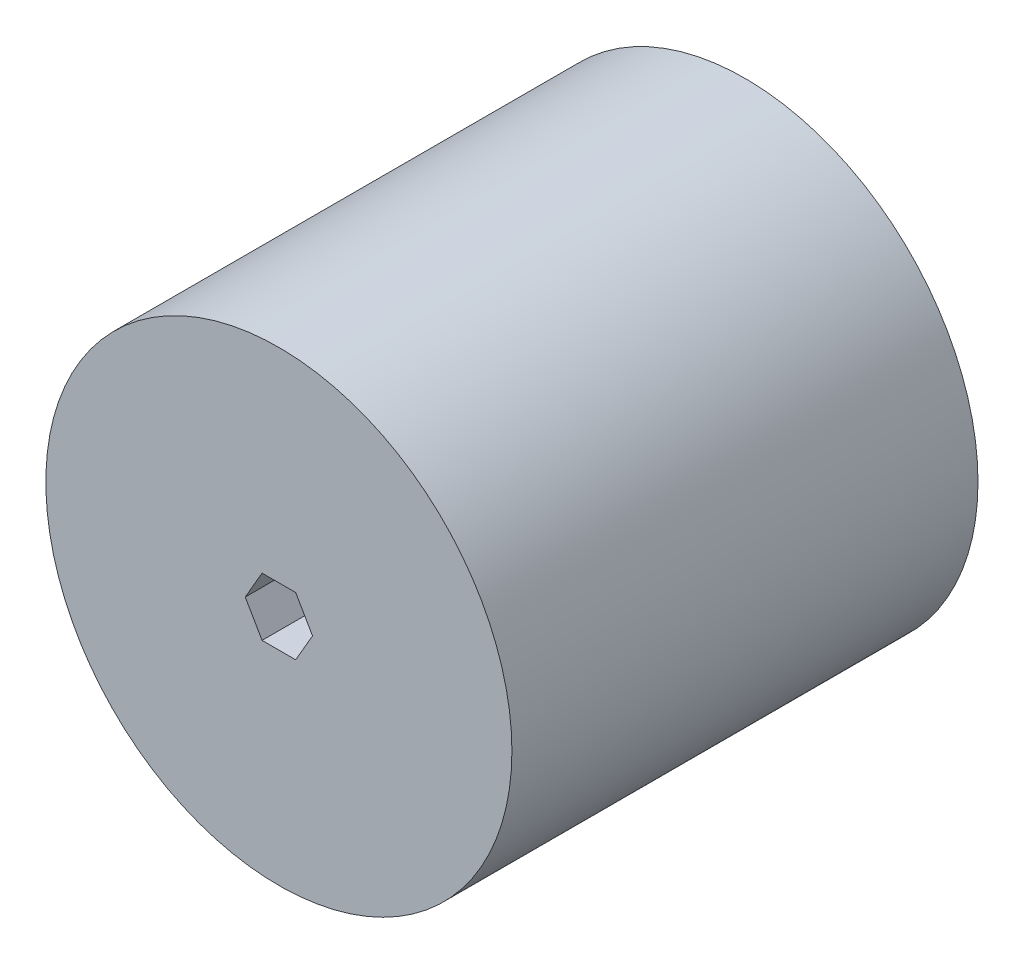
SolidWorks part; units mm, degrees
material "POLYURETHANE (11671)"
ref_plane "Front Plane" through (0, 0, 0) normal (0, 0, 1) x (1, 0, 0)
ref_plane "Top Plane" through (0, 0, 0) normal (0, 1, 0) x (1, 0, 0)
ref_plane "Right Plane" through (0, 0, 0) normal (1, 0, 0) x (0, 0, -1)
sketch "Sketch1" plane through (0, 0, 0) normal (0, 0, 1) x (1, 0, 0)
  line L1 (-7.3323, 0) -> (-3.6662, -6.35)
  line L2 (-3.6662, -6.35) -> (3.6662, -6.35)
  line L3 (3.6662, -6.35) -> (7.3323, 0)
  line L4 (7.3323, 0) -> (3.6662, 6.35)
  line L5 (3.6662, 6.35) -> (-3.6662, 6.35)
  line L6 (-3.6662, 6.35) -> (-7.3323, 0)
  circle A0 centre (0, 0) radius 6.35 construction
  circle A1 centre (0, 0) radius 50.8
  dimension "D1" = 12.7
  dimension "D2" = 101.6
extrude "Boss-Extrude1" add sketch "Sketch1" along normal blind 101.6
